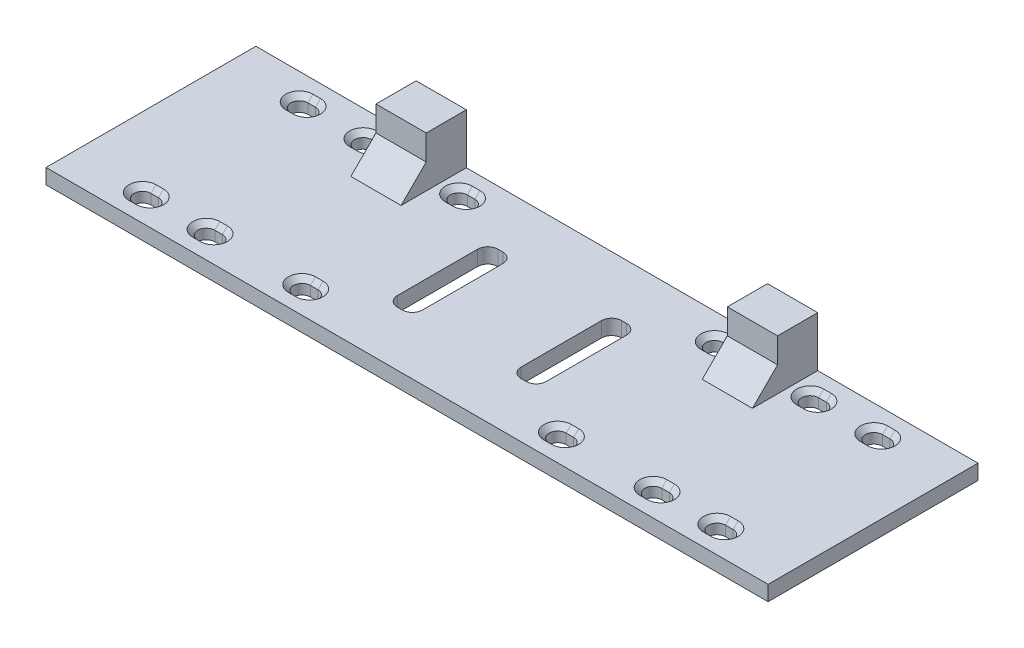
SolidWorks part; units mm, degrees
ref_plane "Front Plane" through (0, 0, 0) normal (0, 0, 1) x (1, 0, 0)
ref_plane "Top Plane" through (0, 0, 0) normal (0, 1, 0) x (1, 0, 0)
ref_plane "Right Plane" through (0, 0, 0) normal (1, 0, 0) x (0, 0, -1)
sketch "Sketch1" plane through (0, 0, 0) normal (0, 1, 0) x (1, 0, 0)
  line L0 (0, 0) -> (-71.9, 0) construction
  line L1 (-71.9, -20.9) -> (71.9, -20.9)
  line L2 (-71.9, -20.9) -> (-71.9, 20.9)
  line L3 (-71.9, 20.9) -> (71.9, 20.9)
  line L4 (71.9, -20.9) -> (71.9, 20.9)
  line L5 (-71.9, -20.9) -> (71.9, 20.9) construction
  line L6 (-71.9, 20.9) -> (71.9, -20.9) construction
  line L8 (0, -20.9) -> (0, 20.9) construction
  circle A0 centre (-57.2125, 15.621) radius 1.5875
  circle A1 centre (-44.5125, 15.621) radius 1.5875
  circle A2 centre (-25.4625, 15.621) radius 1.5875
  circle A3 centre (-25.4625, -15.621) radius 1.5875
  circle A5 centre (-44.5125, -15.621) radius 1.5875
  circle A8 centre (-57.2125, -15.621) radius 1.5875
  circle A9 centre (44.5125, -15.621) radius 1.5875
  circle A10 centre (25.4625, -15.621) radius 1.5875
  circle A11 centre (25.4625, 15.621) radius 1.5875
  circle A12 centre (44.5125, 15.621) radius 1.5875
  circle A13 centre (57.2125, 15.621) radius 1.5875
  circle A14 centre (57.2125, -15.621) radius 1.5875
  point P0 (0, 0)
  dimension "D3" = 143.8
  dimension "D4" = 41.8
extrude "Boss-Extrude1" add sketch "Sketch1" along normal blind 3
sketch "Sketch2" plane through (0, 3, 0) normal (0, 1, 0) x (1, 0, 0)
  line L0 (0, -20.9) -> (0, 20.9) construction
  line L1 (-71.9, -20.9) -> (71.9, -20.9) construction
  line L2 (71.9, 20.9) -> (-71.9, 20.9) construction
  line L3 (71.9, 10.9) -> (31.9, 10.9)
  line L4 (-71.9, 20.9) -> (-31.9, 20.9)
  line L5 (-71.9, 20.9) -> (-71.9, 10.9)
  line L6 (-71.9, 10.9) -> (-31.9, 10.9)
  line L7 (-31.9, 20.9) -> (-31.9, 10.9)
  line L8 (31.9, 20.9) -> (31.9, 10.9)
  line L9 (71.9, 20.9) -> (31.9, 20.9)
  line L10 (71.9, 20.9) -> (71.9, 10.9)
  dimension "D1" = 10
  dimension "D2" = 40
extrude "Boss-Extrude2" [suppressed] add sketch "Sketch2" along normal blind 10
chamfer "Chamfer1" [suppressed] distance 20 angle 27
sketch "Sketch3" plane through (0, 0, -20.9) normal (0, 0, -1) x (-1, 0, 0)
  line L0 (0, 0) -> (0, 22.7681) construction
  line L1 (-55.9, 6.5) -> (55.9, 6.5) construction
  line L2 (-71.9, 3) -> (-71.9, 0) construction
  line L3 (-71.9, 0) -> (71.9, 0) construction
  circle A0 centre (-55.9, 6.5) radius 2.2
  circle A1 centre (55.9, 6.5) radius 2.2
  dimension "D1" = 4.4
  dimension "D2" = 16
  dimension "D3" = 6.5
extrude "Cut-Extrude1" [suppressed] cut sketch "Sketch3" against normal blind 5.2
sketch "Sketch4" plane through (0, 3, 0) normal (0, 1, 0) x (1, 0, 0)
  line L0 (-44.5125, 15.621) -> (-25.4625, 15.621) construction
  line L1 (71.9, 20.9) -> (-71.9, 20.9) construction
  line L2 (-29.9875, 12.9) -> (-39.9875, 12.9)
  line L3 (-29.9875, 12.9) -> (-29.9875, 20.9)
  line L4 (-29.9875, 20.9) -> (-39.9875, 20.9)
  line L5 (-39.9875, 12.9) -> (-39.9875, 20.9)
  line L6 (-34.9875, 15.621) -> (-34.9875, 20.9) construction
  line L7 (29.9875, 20.9) -> (39.9875, 20.9)
  line L8 (0, -20.9) -> (0, 20.9) construction
  line L9 (-71.9, -20.9) -> (71.9, -20.9) construction
  line L10 (39.9875, 12.9) -> (39.9875, 20.9)
  line L11 (29.9875, 12.9) -> (39.9875, 12.9)
  line L12 (29.9875, 12.9) -> (29.9875, 20.9)
  point P4 (-34.9875, 15.621)
  dimension "D1" = 10
  dimension "D2" = 8
extrude "Boss-Extrude3" add sketch "Sketch4" along normal blind 10
chamfer "Chamfer2" distance 5 angle 45 2 edges at (34.9875, 3, -12.9) (-34.9875, 3, -12.9)
sketch "Sketch5" plane through (0, 0, -20.9) normal (0, 0, -1) x (-1, 0, 0)
  line L0 (-34.9875, 13) -> (-34.9875, 0) construction
  line L1 (-39.9875, 13) -> (-29.9875, 13) construction
  line L2 (-71.9, 0) -> (71.9, 0) construction
  line L3 (34.9875, 13) -> (34.9875, 0) construction
  line L4 (29.9875, 13) -> (39.9875, 13) construction
  circle A0 centre (-34.9875, 6.5) radius 2.2
  circle A1 centre (34.9875, 6.5) radius 2.2
  dimension "D1" = 4.4
extrude "Cut-Extrude2" cut sketch "Sketch5" against normal blind 5.2
sketch "Sketch7" plane through (0, 3, 0) normal (0, 1, 0) x (1, 0, 0)
  line L0 (-56.4625, 15.621) -> (-57.9625, 15.621) construction
  line L1 (-56.4625, 13.921) -> (-57.9625, 13.921)
  line L2 (-56.4625, 17.321) -> (-57.9625, 17.321)
  line L3 (-43.7625, 15.621) -> (-45.2625, 15.621) construction
  line L4 (-43.7625, 13.921) -> (-45.2625, 13.921)
  line L5 (-43.7625, 17.321) -> (-45.2625, 17.321)
  line L6 (-26.2125, 15.621) -> (-24.7125, 15.621) construction
  line L7 (-26.2125, 17.321) -> (-24.7125, 17.321)
  line L8 (-26.2125, 13.921) -> (-24.7125, 13.921)
  line L9 (-43.7625, -15.621) -> (-45.2625, -15.621) construction
  line L10 (-43.7625, -17.321) -> (-45.2625, -17.321)
  line L11 (-43.7625, -13.921) -> (-45.2625, -13.921)
  line L12 (-57.9625, -15.621) -> (-56.4625, -15.621) construction
  line L13 (-57.9625, -13.921) -> (-56.4625, -13.921)
  line L14 (-57.9625, -17.321) -> (-56.4625, -17.321)
  line L15 (-24.7125, -15.621) -> (-26.2125, -15.621) construction
  line L16 (-24.7125, -17.321) -> (-26.2125, -17.321)
  line L17 (-24.7125, -13.921) -> (-26.2125, -13.921)
  line L18 (56.4625, -15.621) -> (57.9625, -15.621) construction
  line L19 (56.4625, -13.921) -> (57.9625, -13.921)
  line L20 (56.4625, -17.321) -> (57.9625, -17.321)
  line L21 (45.2625, -15.621) -> (43.7625, -15.621) construction
  line L22 (45.2625, -17.321) -> (43.7625, -17.321)
  line L23 (45.2625, -13.921) -> (43.7625, -13.921)
  line L24 (24.7125, -15.621) -> (26.2125, -15.621) construction
  line L25 (24.7125, -13.921) -> (26.2125, -13.921)
  line L26 (24.7125, -17.321) -> (26.2125, -17.321)
  line L27 (56.4625, 15.621) -> (57.9625, 15.621) construction
  line L28 (56.4625, 17.321) -> (57.9625, 17.321)
  line L29 (56.4625, 13.921) -> (57.9625, 13.921)
  line L30 (43.7625, 15.621) -> (45.2625, 15.621) construction
  line L31 (43.7625, 17.321) -> (45.2625, 17.321)
  line L32 (43.7625, 13.921) -> (45.2625, 13.921)
  line L33 (26.2125, 15.621) -> (24.7125, 15.621) construction
  line L34 (26.2125, 13.921) -> (24.7125, 13.921)
  line L35 (26.2125, 17.321) -> (24.7125, 17.321)
  arc A1 (-56.4625, 13.921) -> (-56.4625, 17.321) centre (-56.4625, 15.621) ccw
  arc A2 (-57.9625, 17.321) -> (-57.9625, 13.921) centre (-57.9625, 15.621) ccw
  arc A4 (-43.7625, 13.921) -> (-43.7625, 17.321) centre (-43.7625, 15.621) ccw
  arc A5 (-45.2625, 17.321) -> (-45.2625, 13.921) centre (-45.2625, 15.621) ccw
  arc A6 (-26.2125, 17.321) -> (-26.2125, 13.921) centre (-26.2125, 15.621) ccw
  arc A7 (-24.7125, 13.921) -> (-24.7125, 17.321) centre (-24.7125, 15.621) ccw
  arc A9 (-43.7625, -17.321) -> (-43.7625, -13.921) centre (-43.7625, -15.621) ccw
  arc A10 (-45.2625, -13.921) -> (-45.2625, -17.321) centre (-45.2625, -15.621) ccw
  arc A11 (-57.9625, -13.921) -> (-57.9625, -17.321) centre (-57.9625, -15.621) ccw
  arc A12 (-56.4625, -17.321) -> (-56.4625, -13.921) centre (-56.4625, -15.621) ccw
  arc A13 (-24.7125, -17.321) -> (-24.7125, -13.921) centre (-24.7125, -15.621) ccw
  arc A14 (-26.2125, -13.921) -> (-26.2125, -17.321) centre (-26.2125, -15.621) ccw
  arc A15 (56.4625, -13.921) -> (56.4625, -17.321) centre (56.4625, -15.621) ccw
  arc A16 (57.9625, -17.321) -> (57.9625, -13.921) centre (57.9625, -15.621) ccw
  arc A17 (45.2625, -17.321) -> (45.2625, -13.921) centre (45.2625, -15.621) ccw
  arc A18 (43.7625, -13.921) -> (43.7625, -17.321) centre (43.7625, -15.621) ccw
  arc A19 (24.7125, -13.921) -> (24.7125, -17.321) centre (24.7125, -15.621) ccw
  arc A20 (26.2125, -17.321) -> (26.2125, -13.921) centre (26.2125, -15.621) ccw
  arc A21 (56.4625, 17.321) -> (56.4625, 13.921) centre (56.4625, 15.621) ccw
  arc A22 (57.9625, 13.921) -> (57.9625, 17.321) centre (57.9625, 15.621) ccw
  arc A23 (43.7625, 17.321) -> (43.7625, 13.921) centre (43.7625, 15.621) ccw
  arc A24 (45.2625, 13.921) -> (45.2625, 17.321) centre (45.2625, 15.621) ccw
  arc A25 (26.2125, 13.921) -> (26.2125, 17.321) centre (26.2125, 15.621) ccw
  arc A26 (24.7125, 17.321) -> (24.7125, 13.921) centre (24.7125, 15.621) ccw
  point P2 (-42.925, -15.621)
  point P4 (-46.9712, -15.621)
  point P5 (-57.2125, 15.621)
  point P11 (-44.5125, 15.621)
  point P13 (-55.7593, 12.4173)
  point P21 (-25.4625, 15.621)
  point P29 (-44.5125, -15.621)
  point P39 (-57.2125, -15.621)
  point P48 (-25.4625, -15.621)
  point P55 (57.2125, -15.621)
  point P63 (44.5125, -15.621)
  point P71 (25.4625, -15.621)
  point P79 (57.2125, 15.621)
  point P87 (44.5125, 15.621)
  point P95 (25.4625, 15.621)
  dimension "D1" = 1.7
  dimension "D2" = 1.5
extrude "Cut-Extrude3" cut sketch "Sketch7" against normal blind 10
chamfer "Chamfer3" distance 1 angle 45 48 edges at (25.4625, 3, 17.321) (27.9125, 3, 15.621) (23.0125, 3, 15.621) (25.4625, 3, 13.921) (42.0625, 3, 15.621) (44.5125, 3, 17.321) (44.5125, 3, 13.921) (46.9625, 3, 15.621) (59.6625, 3, 15.621) (57.2125, 3, 13.921) (57.2125, 3, 17.321) (54.7625, 3, 15.621) (54.7625, 3, -15.621) (57.2125, 3, -13.921) (57.2125, 3, -17.321) (59.6625, 3, -15.621) (46.9625, 3, -15.621) (44.5125, 3, -17.321) (44.5125, 3, -13.921) (42.0625, 3, -15.621) (25.4625, 3, -13.921) (27.9125, 3, -15.621) (23.0125, 3, -15.621) (25.4625, 3, -17.321) (-27.9125, 3, 15.621) (-25.4625, 3, 17.321) (-25.4625, 3, 13.921) (-23.0125, 3, 15.621) (-23.0125, 3, -15.621) (-25.4625, 3, -17.321) (-25.4625, 3, -13.921) (-27.9125, 3, -15.621) (-54.7625, 3, 15.621) (-57.2125, 3, 13.921) (-57.2125, 3, 17.321) (-59.6625, 3, 15.621) (-44.5125, 3, 17.321) (-42.0625, 3, 15.621) (-46.9625, 3, 15.621) (-44.5125, 3, 13.921) (-42.0625, 3, -15.621) (-44.5125, 3, -17.321) (-44.5125, 3, -13.921) (-46.9625, 3, -15.621) (-57.2125, 3, -13.921) (-54.7625, 3, -15.621) (-59.6625, 3, -15.621) (-57.2125, 3, -17.321)
sketch "Sketch8" plane through (0, 3, 0) normal (0, 1, 0) x (1, 0, 0)
  line L0 (0, 0) -> (0, -8.8909) construction
  line L1 (0, 0) -> (-12.3261, 0) construction
  line L2 (14.8261, 10) -> (9.8261, 10)
  line L3 (-14.8261, -10) -> (-9.8261, -10)
  line L4 (-14.8261, -10) -> (-14.8261, 10)
  line L5 (-14.8261, 10) -> (-9.8261, 10)
  line L6 (-9.8261, -10) -> (-9.8261, 10)
  line L7 (-14.8261, -10) -> (-9.8261, 10) construction
  line L8 (-14.8261, 10) -> (-9.8261, -10) construction
  line L9 (9.8261, -10) -> (9.8261, 10)
  line L10 (14.8261, -10) -> (9.8261, -10)
  line L11 (14.8261, -10) -> (14.8261, 10)
  dimension "D1" = 20
  dimension "D2" = 5
extrude "Cut-Extrude4" cut sketch "Sketch8" against normal blind 10
fillet "Fillet1" radius 2 8 edges at (9.8261, 1.5, 10) (14.8261, 1.5, 10) (14.8261, 1.5, -10) (9.8261, 1.5, -10) (-9.8261, 1.5, 10) (-14.8261, 1.5, 10) (-9.8261, 1.5, -10) (-14.8261, 1.5, -10)
equation "\"width\"=50"
